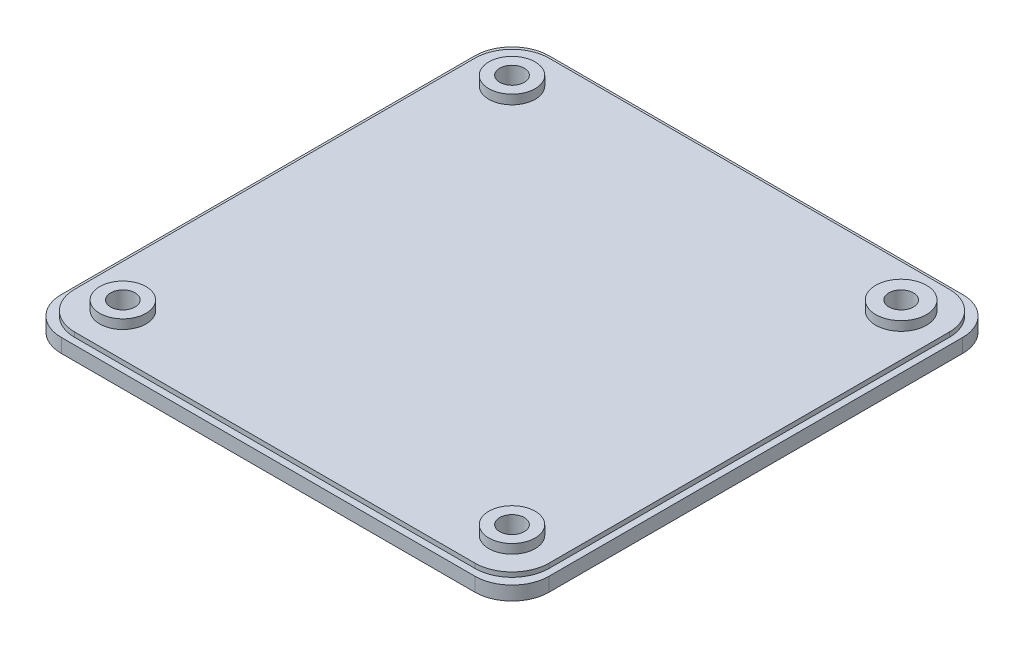
SolidWorks part; units mm, degrees
ref_plane "Front Plane" through (0, 0, 0) normal (0, 0, 1) x (1, 0, 0)
ref_plane "Top Plane" through (0, 0, 0) normal (0, 1, 0) x (1, 0, 0)
ref_plane "Right Plane" through (0, 0, 0) normal (1, 0, 0) x (0, 0, -1)
sketch "Baseplate" plane through (0, 0, 0) normal (0, 1, 0) x (1, 0, 0)
  line L5 (0, 0) -> (105.3, 0)
  line L6 (0, 0) -> (0, -105.3)
  line L7 (0, -105.3) -> (105.3, -105.3)
  line L8 (105.3, 0) -> (105.3, -105.3)
  dimension "D1" = 105.3
  dimension "D2" = 105.3
extrude "Boss-Extrude1" add sketch "Baseplate" along normal blind 4
sketch "Stands" plane through (0, 4, 0) normal (0, 1, 0) x (1, 0, 0)
  line L0 (10.65, -10.65) -> (10.65, 0) construction
  line L1 (105.3, 0) -> (0, 0) construction
  line L2 (10.65, -10.65) -> (0, -10.65) construction
  line L3 (10.65, -10.65) -> (94.65, -10.65) construction
  line L4 (0, 0) -> (0, -105.3) construction
  line L5 (10.65, -10.65) -> (10.65, -94.65) construction
  line L6 (10.65, -94.65) -> (94.65, -94.65) construction
  circle A0 centre (10.65, -10.65) radius 5
  circle A1 centre (94.65, -10.65) radius 5.48
  circle A2 centre (10.65, -94.65) radius 5
  circle A3 centre (94.65, -94.65) radius 5
  dimension "D1" = 10
  dimension "D2" = 10.9599
  dimension "D6" = 10
  dimension "D7" = 10
  dimension "D3" = 10.65
  dimension "D4" = 10.65
  dimension "D5" = 84
  dimension "D8" = 84
  dimension "D9" = 84
extrude "Boss-Extrude3" add sketch "Stands" along normal blind 2
sketch "Mounting_Holes" plane through (0, 6, 0) normal (0, 1, 0) x (1, 0, 0)
  circle A2 centre (10.65, -10.65) radius 2.65
  circle A3 centre (10.65, -10.65) radius 5 construction
  circle A4 centre (94.65, -10.65) radius 2.65
  circle A5 centre (94.65, -10.65) radius 5.48 construction
  circle A6 centre (94.65, -94.65) radius 2.65
  circle A7 centre (94.65, -94.65) radius 5 construction
  circle A8 centre (10.65, -94.65) radius 2.65
  circle A9 centre (10.65, -94.65) radius 5 construction
  dimension "D1" = 5.3
  dimension "D2" = 5.3
  dimension "D3" = 5.3
  dimension "D4" = 5.3
extrude "Cut-Extrude1" cut sketch "Mounting_Holes" against normal up to next
sketch "Edge_Cutout" plane through (0, 4, 0) normal (0, 1, 0) x (1, 0, 0)
  line L4 (105.3, -105.3) -> (105.3, 0) construction
  line L5 (0, 0) -> (105.3, 0)
  line L6 (0, 0) -> (0, -105.3)
  line L7 (0, -105.3) -> (105.3, -105.3)
  line L8 (105.3, 0) -> (105.3, -105.3)
  line L9 (0, -105.3) -> (105.3, -105.3) construction
  line L10 (1.45, -1.45) -> (1.45, 0) construction
  line L11 (1.45, -1.45) -> (103.85, -1.45)
  line L12 (1.45, -1.45) -> (1.45, -103.85)
  line L13 (1.45, -103.85) -> (103.85, -103.85)
  line L14 (103.85, -1.45) -> (103.85, -103.85)
  line L15 (1.45, -1.45) -> (0, -1.45) construction
  line L16 (103.85, -103.85) -> (105.3, -103.85) construction
  line L17 (103.85, -103.85) -> (103.85, -105.3) construction
  dimension "D1" = 1.45
  dimension "D2" = 1.45
  dimension "D3" = 1.45
  dimension "D4" = 1.45
extrude "Cut-Extrude2" cut sketch "Edge_Cutout" against normal blind 1
fillet "Fillet_Edges" radius 8 8 edges at (0, 1.5, 0) (105.3, 1.5, 0) (105.3, 1.5, 105.3) (0, 1.5, 105.3) (103.85, 3.5, 1.45) (103.85, 3.5, 103.85) (1.45, 3.5, 103.85) (1.45, 3.5, 1.45)
equation "\"wall_thickness\"= 1.35mm"
equation "\"sidewall_padding\" = 1.3mm"
equation "\"D1@Baseplate\"=100+2*\"wall_thickness\"+2*\"sidewall_padding\""
equation "\"D2@Baseplate\"=100+2*\"wall_thickness\"+2*\"sidewall_padding\""
equation "\"D4@Stands\"=\"wall_thickness\"+\"sidewall_padding\"+8"
equation "\"D3@Stands\"=\"wall_thickness\"+\"sidewall_padding\"+8"
equation "\"D2@Edge_Cutout\"=\"wall_thickness\" + 0.10"
equation "\"D1@Edge_Cutout\"=\"wall_thickness\" + 0.10"
equation "\"D4@Edge_Cutout\"=\"wall_thickness\" + 0.10"
equation "\"D3@Edge_Cutout\"=\"wall_thickness\" + 0.10"
